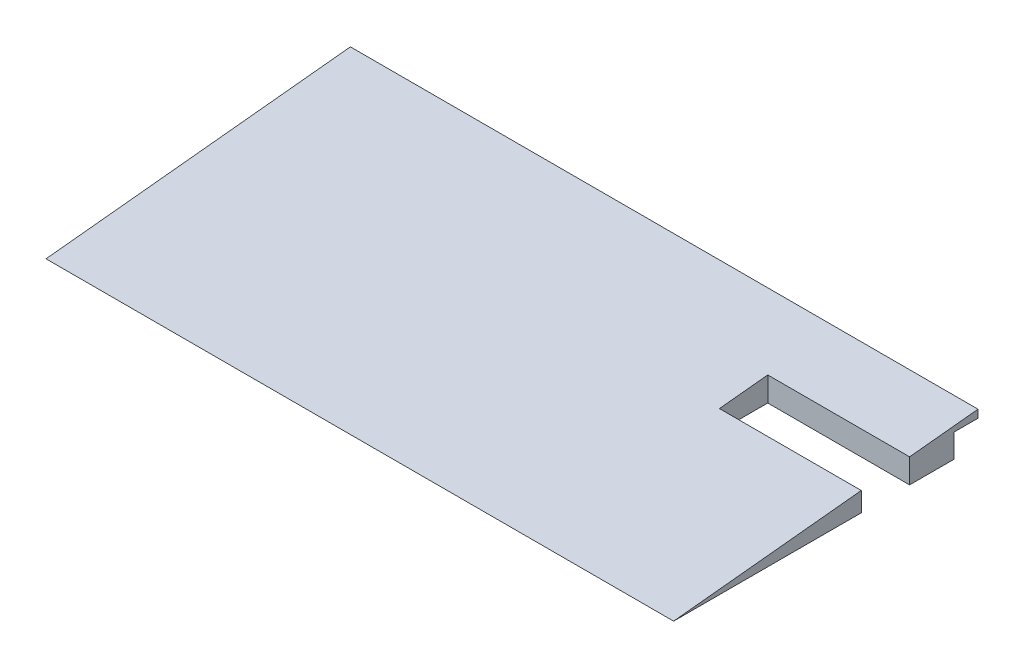
SolidWorks part; units mm, degrees
ref_plane "Front Plane" through (0, 0, 0) normal (0, 0, 1) x (1, 0, 0)
ref_plane "Top Plane" through (0, 0, 0) normal (0, 1, 0) x (1, 0, 0)
ref_plane "Right Plane" through (0, 0, 0) normal (1, 0, 0) x (0, 0, -1)
sketch "Sketch1" plane through (0, 0, 0) normal (1, 0, 0) x (0, 0, -1)
  line L0 (-48.5, 0) -> (48.5, 10)
  line L1 (48.5, 0) -> (-48.5, 0)
  line L5 (0, 55) -> (0, -55) construction
  line L6 (55, 0) -> (-55, 0) construction
  line L7 (48.5, 10) -> (48.5, 0)
  point P0 (0, 0)
  point P3 (0, 0)
  dimension "D2" = 10
  dimension "D3" = 97
extrude "Boss-Extrude1" add sketch "Sketch1" along normal mid plane 200
sketch "Sketch3" plane through (100, 0, 0) normal (1, 0, 0) x (0, 0, -1)
  line L0 (55, 0) -> (-55, 0) construction
  line L1 (48.5, 0) -> (40.8, 0)
  line L2 (48.5, 0) -> (48.5, 7.5)
  line L3 (48.5, 7.5) -> (40.8, 7.5)
  line L4 (40.8, 0) -> (40.8, 7.5)
  line L5 (48.5, 0) -> (48.5, 10) construction
  dimension "D1" = 7.7
  dimension "D2" = 7.5
extrude "Cut-Extrude1" cut sketch "Sketch3" against normal through all
ref_plane "Plane1" through (100, 0, -40.8) normal (0, 0, -1) x (-1, 0, 0)
sketch "Sketch6" plane through (0, 0, 0) normal (0, 1, 0) x (1, 0, 0)
  line L0 (100, 11.5) -> (100, 26.5) construction
  line L1 (100, 26.7) -> (54.8, 26.7)
  line L2 (100, 26.7) -> (100, 11.3)
  line L3 (100, 11.3) -> (54.8, 11.3)
  line L4 (54.8, 26.7) -> (54.8, 11.3)
  line L5 (100, 19) -> (54.8, 19) construction
  point P0 (100, 26.5)
  point P2 (100, 11.5)
  dimension "D1" = 45.2
  dimension "D2" = 15.4
extrude "Cut-Extrude2" cut sketch "Sketch6" along normal through all
